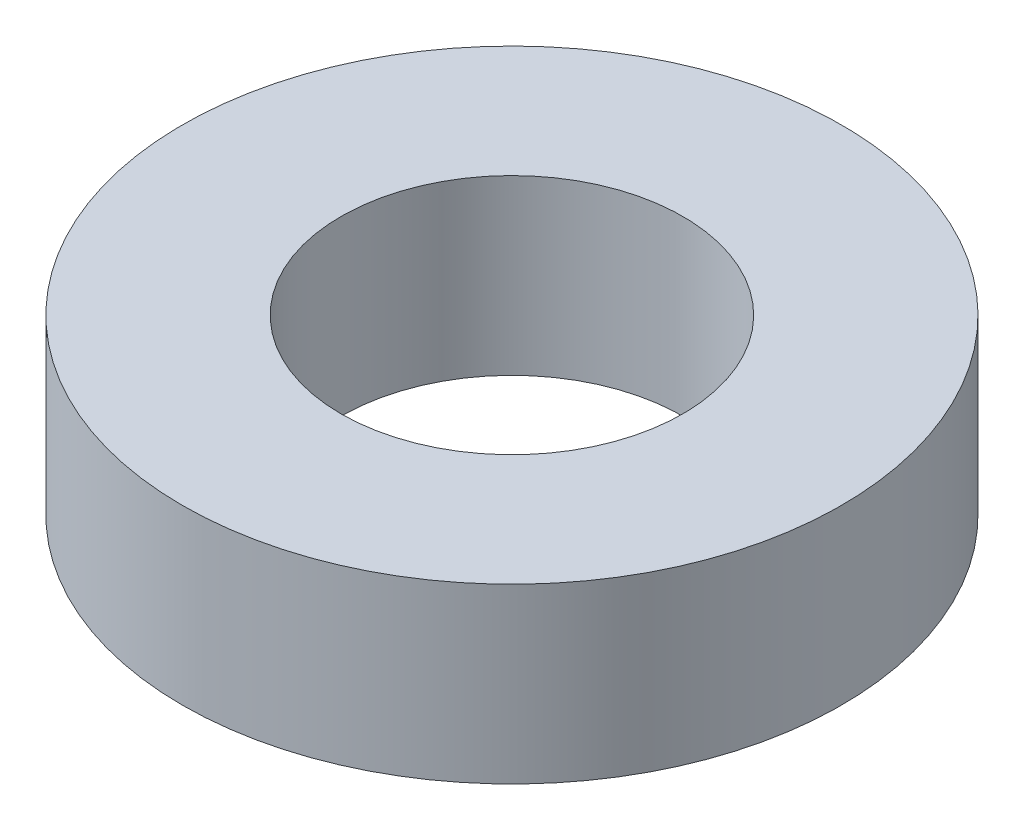
SolidWorks part; units mm, degrees
ref_plane "Front Plane" through (0, 0, 0) normal (0, 0, 1) x (1, 0, 0)
ref_plane "Top Plane" through (0, 0, 0) normal (0, 1, 0) x (1, 0, 0)
ref_plane "Right Plane" through (0, 0, 0) normal (1, 0, 0) x (0, 0, -1)
sketch "Sketch1" plane through (0, 0, 0) normal (0, 1, 0) x (1, 0, 0)
  circle A0 centre (0, 0) radius 4.15
  circle A1 centre (0, 0) radius 8
  dimension "D1" = 8.3
  dimension "D2" = 16
extrude "Boss-Extrude1" add sketch "Sketch1" along normal blind 4.2
